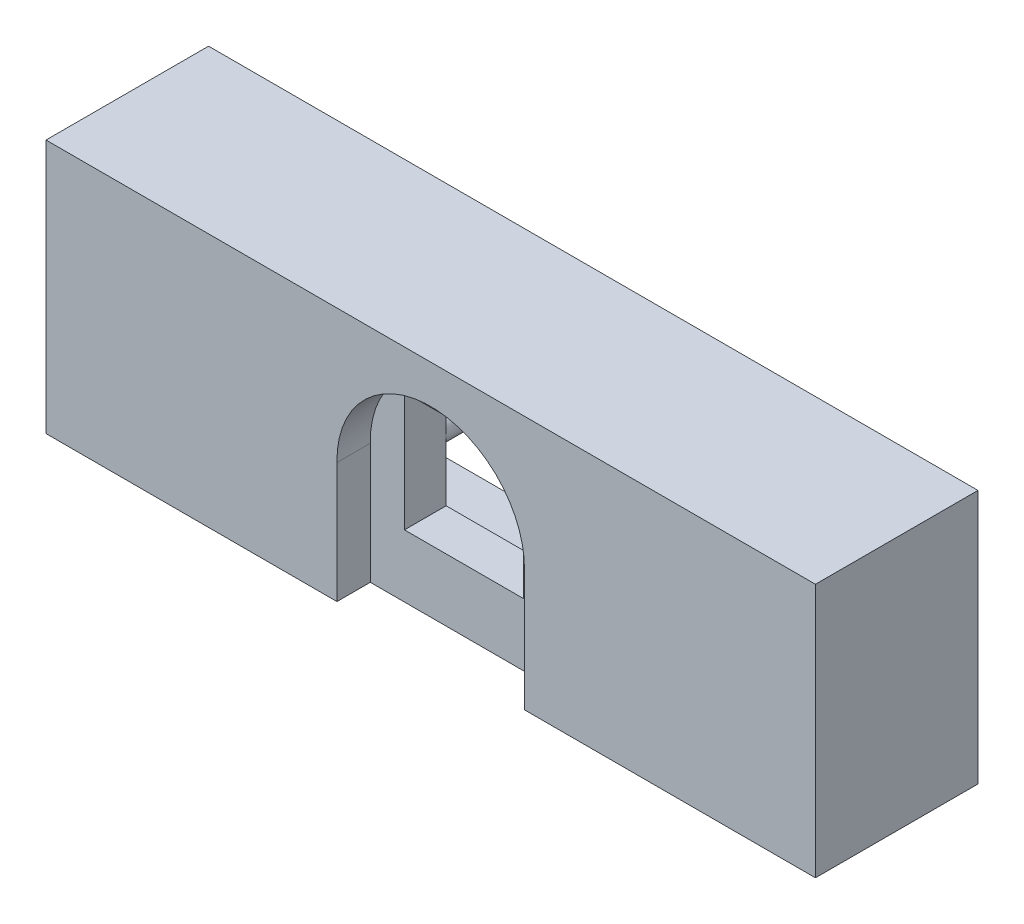
SolidWorks part; units mm, degrees
ref_plane "Front Plane" through (0, 0, 0) normal (0, 0, 1) x (1, 0, 0)
ref_plane "Top Plane" through (0, 0, 0) normal (0, 1, 0) x (1, 0, 0)
ref_plane "Right Plane" through (0, 0, 0) normal (1, 0, 0) x (0, 0, -1)
sketch "Sketch1" plane through (0, 0, 0) normal (0, 0, 1) x (1, 0, 0)
  line L0 (-12.15, 12.15) -> (12.15, 12.15)
  line L1 (-7.15, 7.15) -> (7.15, 7.15)
  line L2 (-7.15, 7.15) -> (-7.15, -7.15)
  line L3 (-7.15, -7.15) -> (7.15, -7.15)
  line L4 (7.15, 7.15) -> (7.15, -7.15)
  line L5 (-7.15, 7.15) -> (7.15, -7.15) construction
  line L6 (-7.15, -7.15) -> (7.15, 7.15) construction
  line L7 (12.15, 12.15) -> (12.15, -12.15)
  line L8 (-12.15, -12.15) -> (12.15, -12.15)
  line L9 (-12.15, 12.15) -> (-12.15, -12.15)
  point P0 (0, 0)
  dimension "D1" = 14.3
  dimension "D2" = 14.3
  dimension "D3" = 5
extrude "Boss-Extrude1" add sketch "Sketch1" along normal blind 4
sketch "Sketch3" plane through (0, 0, 0) normal (0, 0, -1) x (-1, 0, 0)
  line L0 (0, 0) -> (0, 18.9247) construction
  line L1 (7.15, 0) -> (12.15, 0) construction
  line L2 (7.15, 7.15) -> (7.15, -7.15) construction
  line L3 (12.15, 12.15) -> (12.15, -12.15) construction
  circle A0 centre (8.75, 0) radius 1.5
  circle A1 centre (-8.75, 0) radius 1.5
  point P13 (0, 0)
  point P14 (0, 0)
  dimension "D1" = 1.6
extrude "Boss-Extrude4" add sketch "Sketch3" along normal blind 4
sketch "Sketch4" plane through (0, 0, 4) normal (0, 0, 1) x (1, 0, 0)
  line L0 (11.2482, -0.2018) -> (11.2482, -11.15)
  line L1 (-11.2482, -0.2018) -> (-11.2482, -11.15)
  line L2 (-11.2482, -11.15) -> (-14.15, -11.15)
  line L3 (-14.15, -11.15) -> (-14.15, 13.85)
  line L4 (-14.15, 13.85) -> (14.15, 13.85)
  line L5 (11.2482, -11.15) -> (14.15, -11.15)
  line L6 (14.15, -11.15) -> (14.15, 13.85)
  arc A1 (11.2482, -0.2018) -> (-11.2482, -0.2018) centre (0, 0) ccw
extrude "Boss-Extrude5" add sketch "Sketch4" along normal blind 4
sketch "Sketch5" plane through (0, 0, 0) normal (0, 1, 0) x (1, 0, 0)
  line L0 (-12.15, 0) -> (-14.15, -4)
  line L1 (-14.15, -4) -> (-12.15, -4)
  line L2 (-12.15, -4) -> (-12.15, 0)
  line L3 (12.15, 0) -> (12.15, -4)
  line L4 (12.15, -4) -> (14.15, -4)
  line L5 (14.15, -4) -> (12.15, 0)
extrude "Boss-Extrude6" add sketch "Sketch5" along normal up to surface and the other way up to surface up to face at (0, 12.15, 2) other way up to face at (12.5893, -11.15, 5.6)
sketch "Sketch6" plane through (0, 0, 4) normal (0, 0, 1) x (1, 0, 0)
  line L0 (-14.15, -11.15) -> (-17.465, -11.15)
  line L1 (-17.465, -11.15) -> (-17.465, -14.475)
  line L2 (-17.465, -14.475) -> (16.8484, -14.475)
  line L3 (16.8484, -14.475) -> (16.8484, -10.7389)
  line L4 (16.8484, -10.7389) -> (14.15, -11.15)
  line L5 (14.15, -11.15) -> (-14.15, -11.15)
extrude "Cut-Extrude1" cut sketch "Sketch6" against normal blind 11
sketch "Sketch7" plane through (0, 0, 0) normal (0, 0, -1) x (-1, 0, 0)
  line L4 (-7.15, 7.15) -> (7.15, 7.15) construction
  line L5 (-7.15, -7.15) -> (-7.15, 7.15) construction
  line L6 (7.15, -7.15) -> (-7.15, -7.15) construction
  line L7 (7.15, 7.15) -> (7.15, -7.15) construction
  line L8 (-12.15, 12.15) -> (-12.15, -11.15)
  line L9 (-12.15, -11.15) -> (12.15, -11.15)
  line L10 (12.15, -11.15) -> (12.15, 12.15)
  line L11 (12.15, 12.15) -> (-12.15, 12.15)
  line L16 (-12.15, 12.15) -> (-12.15, -11.15)
  line L17 (-12.15, -11.15) -> (12.15, -11.15)
  line L18 (12.15, -11.15) -> (12.15, 12.15)
  line L19 (12.15, 12.15) -> (-12.15, 12.15)
  line L20 (-7.15, 7.15) -> (7.15, 7.15)
  line L21 (-7.15, -7.15) -> (-7.15, 7.15)
  line L22 (7.15, -7.15) -> (-7.15, -7.15)
  line L23 (7.15, 7.15) -> (7.15, -7.15)
  dimension "D1" = 0
extrude "Boss-Extrude8" add sketch "Sketch7" along normal blind 1
sketch "Sketch8" plane through (0, -11.15, 0) normal (0, -1, 0) x (1, 0, 0)
  line L12 (-14.15, 4) -> (-12.15, 0)
  line L13 (-12.15, 0) -> (-12.15, -1)
  line L14 (-12.15, -1) -> (12.15, -1)
  line L15 (12.15, -1) -> (12.15, 0)
  line L16 (12.15, 0) -> (14.15, 4)
  line L17 (14.15, 4) -> (14.15, 8)
  line L18 (14.15, 8) -> (11.2482, 8)
  line L19 (11.2482, 8) -> (11.2482, 4)
  line L20 (11.2482, 4) -> (-11.2482, 4)
  line L21 (-11.2482, 4) -> (-11.2482, 8)
  line L22 (-11.2482, 8) -> (-14.15, 8)
  line L23 (-14.15, 8) -> (-14.15, 4)
  line L24 (-14.15, 4) -> (-12.15, 0)
  line L25 (-12.15, 0) -> (-12.15, -1)
  line L26 (-12.15, -1) -> (12.15, -1)
  line L27 (12.15, -1) -> (12.15, 0)
  line L28 (12.15, 0) -> (14.15, 4)
  line L29 (14.15, 4) -> (14.15, 8)
  line L30 (14.15, 8) -> (11.2482, 8)
  line L31 (11.2482, 8) -> (11.2482, 4)
  line L32 (11.2482, 4) -> (-11.2482, 4)
  line L33 (-11.2482, 4) -> (-11.2482, 8)
  line L34 (-11.2482, 8) -> (-14.15, 8)
  line L35 (-14.15, 8) -> (-14.15, 4)
  dimension "D1" = 0
extrude "Boss-Extrude9" add sketch "Sketch8" along normal blind 1.5
sketch "Sketch9" plane through (0, -12.65, 0) normal (0, -1, 0) x (1, 0, 0)
  line L0 (-14.15, 8) -> (-42.15, 8) construction
  line L1 (-42.15, 4) -> (-42.15, -11.5)
  line L3 (14.15, 8) -> (42.15, 8) construction
  line L4 (42.15, 4) -> (42.15, -11.5)
  line L5 (-14.15, 4) -> (-42.15, 4)
  line L6 (14.15, 4) -> (42.15, 4)
  line L7 (-14.15, 8) -> (-46.15, 8)
  line L8 (-46.15, 8) -> (-46.15, -11.5)
  line L9 (14.15, 8) -> (46.15, 8)
  line L10 (46.15, 8) -> (46.15, -11.5)
  line L11 (-46.15, -11.5) -> (-42.15, -11.5)
  line L12 (42.15, -11.5) -> (46.15, -11.5)
  line L13 (-14.15, 8) -> (-14.15, 4)
  line L14 (14.15, 4) -> (14.15, 8)
  dimension "D1" = 28
  dimension "D2" = 19.5
  dimension "D3" = 4
extrude "Boss-Extrude10" add sketch "Sketch9" against normal up to surface (26.5 mm away) up to face at (0, 13.85, 6)
sketch "Sketch10" plane through (0, 13.85, 0) normal (0, 1, 0) x (1, 0, 0)
  line L12 (42.15, -4) -> (-42.15, -4)
  line L13 (-42.15, -4) -> (-42.15, 11.5)
  line L14 (-42.15, 11.5) -> (-46.15, 11.5)
  line L15 (-46.15, 11.5) -> (-46.15, -8)
  line L16 (-46.15, -8) -> (46.15, -8)
  line L17 (46.15, -8) -> (46.15, 11.5)
  line L18 (46.15, 11.5) -> (42.15, 11.5)
  line L19 (42.15, 11.5) -> (42.15, -4)
  line L22 (-42.15, 11.5) -> (-46.15, 11.5)
  line L23 (-46.15, 11.5) -> (-46.15, -8)
  line L24 (-46.15, -8) -> (46.15, -8)
  line L25 (46.15, -8) -> (46.15, 11.5)
  line L26 (46.15, 11.5) -> (-42.15, 11.5)
  dimension "D1" = 0
extrude "Boss-Extrude11" add sketch "Sketch10" along normal blind 2
sketch "Sketch11" plane through (0, -12.65, 0) normal (0, -1, 0) x (1, 0, 0)
  line L18 (-11.2482, 8) -> (-46.15, 8)
  line L19 (-46.15, 8) -> (-46.15, -11.5)
  line L20 (-46.15, -11.5) -> (-42.15, -11.5)
  line L21 (-42.15, -11.5) -> (-42.15, 4)
  line L22 (-42.15, 4) -> (-14.15, 4)
  line L23 (-14.15, 4) -> (-12.15, 0)
  line L24 (-12.15, 0) -> (-12.15, -1)
  line L25 (-12.15, -1) -> (12.15, -1)
  line L26 (12.15, -1) -> (12.15, 0)
  line L27 (12.15, 0) -> (14.15, 4)
  line L28 (14.15, 4) -> (42.15, 4)
  line L29 (42.15, 4) -> (42.15, -11.5)
  line L30 (42.15, -11.5) -> (46.15, -11.5)
  line L31 (46.15, -11.5) -> (46.15, 8)
  line L32 (46.15, 8) -> (11.2482, 8)
  line L33 (11.2482, 8) -> (11.2482, 4)
  line L34 (11.2482, 4) -> (-11.2482, 4)
  line L35 (-11.2482, 4) -> (-11.2482, 8)
  line L36 (-11.2482, 8) -> (-46.15, 8)
  line L37 (-46.15, 8) -> (-46.15, -11.5)
  line L38 (-46.15, -11.5) -> (42.15, -11.5)
  line L48 (42.15, -11.5) -> (46.15, -11.5)
  line L49 (46.15, -11.5) -> (46.15, 8)
  line L50 (46.15, 8) -> (11.2482, 8)
  line L51 (11.2482, 8) -> (11.2482, 4)
  line L52 (11.2482, 4) -> (-11.2482, 4)
  line L53 (-11.2482, 4) -> (-11.2482, 8)
  dimension "D1" = 0
extrude "Boss-Extrude12" add sketch "Sketch11" along normal blind 2
sketch "Sketch12" plane through (0, -14.65, 0) normal (0, -1, 0) x (1, 0, 0)
  line L0 (11.2482, 4) -> (26.2482, 4) construction
  line L1 (26.2482, 4) -> (26.2482, -11.5) construction
  line L2 (46.15, -11.5) -> (26.2482, -11.5) construction
  circle A1 centre (26.2482, -7.5) radius 1.6
  point P7 (0, 0)
  dimension "D1" = 3.2
  dimension "D2" = 4
extrude "Cut-Extrude2" cut sketch "Sketch12" against normal blind 2
sketch "Sketch13" plane through (0, 0, -11.5) normal (0, 0, -1) x (-1, 0, 0)
  line L0 (42.15, -12.65) -> (-42.15, -12.65) construction
  line L1 (42.15, 13.85) -> (42.15, -12.65) construction
  line L2 (-42.15, 13.85) -> (42.15, 13.85) construction
  line L3 (-42.15, 13.85) -> (-42.15, -12.65) construction
  line L4 (46.15, -14.65) -> (46.15, 15.85)
  line L5 (46.15, 15.85) -> (-46.15, 15.85)
  line L6 (-46.15, 15.85) -> (-46.15, -14.65)
  line L7 (-46.15, -14.65) -> (46.15, -14.65)
  line L8 (46.15, -14.65) -> (46.15, 15.85)
  line L9 (46.15, 15.85) -> (-46.15, 15.85)
  line L10 (-46.15, 15.85) -> (-46.15, -14.65)
  line L11 (-46.15, -14.65) -> (46.15, -14.65)
  line L12 (42.15, -12.65) -> (-42.15, -12.65)
  line L13 (42.15, 13.85) -> (42.15, -12.65)
  line L14 (-42.15, 13.85) -> (42.15, 13.85)
  line L15 (-42.15, 13.85) -> (-42.15, -12.65)
  dimension "D1" = 0
